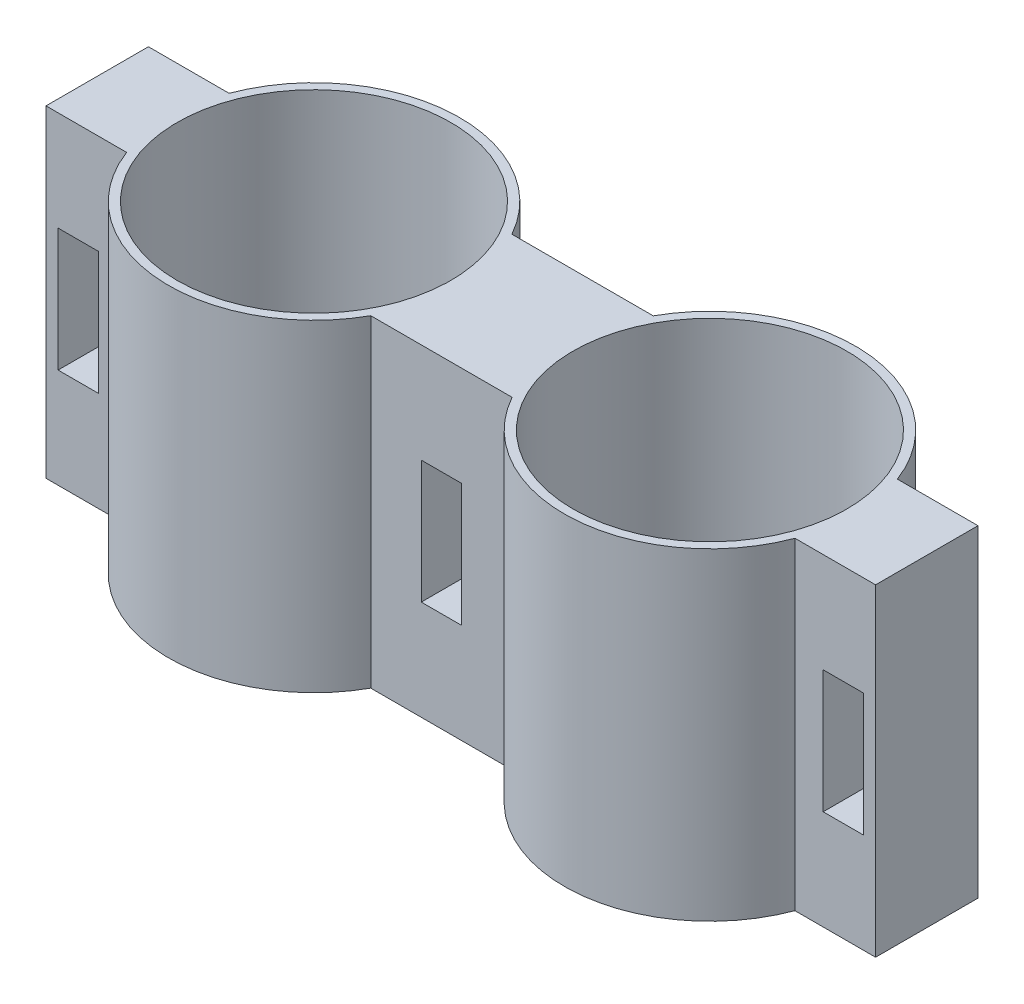
SolidWorks part; units mm, degrees
ref_plane "Front Plane" through (0, 0, 0) normal (0, 0, 1) x (1, 0, 0)
ref_plane "Top Plane" through (0, 0, 0) normal (0, 1, 0) x (1, 0, 0)
ref_plane "Right Plane" through (0, 0, 0) normal (1, 0, 0) x (0, 0, -1)
sketch "Sketch1" plane through (0, 0, 0) normal (0, 1, 0) x (1, 0, 0)
  line L0 (-49.0921, 0) -> (49.0921, 0) construction
  line L1 (-20, 17.5) -> (-20, -17.5) construction
  line L2 (-17.5289, -17.5) -> (17.5289, -17.5) construction
  line L3 (20, -17.5) -> (20, 17.5) construction
  line L4 (17.5289, 17.5) -> (-17.5289, 17.5) construction
  line L5 (-17.5289, 17.5) -> (17.5289, 17.5)
  line L6 (-17.5289, -17.5) -> (17.5289, -17.5)
  line L7 (-17.5289, 17.5) -> (17.5289, -17.5) construction
  line L8 (0, 17.5) -> (0, -17.5) construction
  line L9 (-82.8738, -12.7) -> (-82.8738, 12.7) construction
  line L10 (-82.8738, -12.7) -> (-102.8738, -12.7)
  line L11 (-82.8738, -12.7) -> (-82.8738, 12.7)
  line L12 (-82.8738, 12.7) -> (-102.8738, 12.7)
  line L13 (-102.8738, -12.7) -> (-102.8738, 12.7)
  line L14 (82.8738, -12.7) -> (82.8738, 12.7)
  line L15 (82.8738, -12.7) -> (102.8738, -12.7)
  line L16 (82.8738, 12.7) -> (102.8738, 12.7)
  line L17 (102.8738, -12.7) -> (102.8738, 12.7)
  arc A0 (-17.5289, 17.5) -> (-17.5289, -17.5) centre (-49.0921, 0) ccw
  arc A1 (-20, 17.5) -> (-20, -17.5) centre (-49.0921, 0) ccw
  arc A2 (20, -17.5) -> (20, 17.5) centre (49.0921, 0) ccw
  arc A3 (17.5289, -17.5) -> (17.5289, 17.5) centre (49.0921, 0) ccw
  point P21 (0, -17.5)
  dimension "D3" = 67.9
  dimension "D4" = 2.14
  dimension "D5" = 67.9
  dimension "D6" = 2.14
  dimension "D1" = 40
  dimension "D2" = 35
  dimension "D7" = 98.1843
  dimension "D8" = 35
  dimension "D9" = 35.0578
  dimension "D10" = 25.4
  dimension "D11" = 20
  dimension "D12" = 35
extrude "Boss-Extrude1" add sketch "Sketch1" along normal blind 80 contours A0 L6 A3 L5 | L11 L10 L13 L12 | L14 L16 L17 L15
sketch "Sketch2" plane through (0, 80, 0) normal (0, 1, 0) x (1, 0, 0)
  line L0 (-49.1082, 0) -> (49.0921, 0) construction
  circle A0 centre (-49.1082, 0) radius 33.95
  circle A1 centre (49.0921, 0) radius 33.95
  dimension "D1" = 67.9
  dimension "D2" = 98.2003
extrude "Cut-Extrude1" cut sketch "Sketch2" against normal blind 80
sketch "Sketch3" plane through (0, 0, 12.7) normal (0, 0, 1) x (1, 0, 0)
  line L0 (-94.8738, 80) -> (-94.8738, 0) construction
  line L2 (-5, 24.75) -> (5, 24.75)
  line L3 (0, 80) -> (0, 0) construction
  line L4 (-17.5289, 80) -> (17.5289, 80) construction
  line L5 (-5, 24.75) -> (-5, 55.25)
  line L6 (-82.8738, 80) -> (-102.8738, 80) construction
  line L7 (-82.8738, 0) -> (-102.8738, 0) construction
  line L8 (-102.8738, 80) -> (-102.8738, 0) construction
  line L9 (94.8738, 80) -> (94.8738, 0) construction
  line L10 (-99.8738, 24.75) -> (-89.8738, 24.75)
  line L11 (-99.8738, 24.75) -> (-99.8738, 55.25)
  line L12 (-99.8738, 55.25) -> (-89.8738, 55.25)
  line L13 (-89.8738, 24.75) -> (-89.8738, 55.25)
  line L14 (-99.8738, 24.75) -> (-89.8738, 55.25) construction
  line L15 (-99.8738, 55.25) -> (-89.8738, 24.75) construction
  line L16 (99.8738, 24.75) -> (89.8738, 55.25) construction
  line L17 (99.8738, 55.25) -> (89.8738, 24.75) construction
  line L18 (99.8738, 24.75) -> (89.8738, 24.75)
  line L19 (99.8738, 24.75) -> (99.8738, 55.25)
  line L20 (89.8738, 24.75) -> (89.8738, 55.25)
  line L21 (99.8738, 55.25) -> (89.8738, 55.25)
  line L22 (-5, 55.25) -> (5, 55.25)
  line L23 (5, 24.75) -> (5, 55.25)
  line L24 (-5, 24.75) -> (5, 55.25) construction
  line L25 (-5, 55.25) -> (5, 24.75) construction
  point P13 (-94.8738, 40)
  point P24 (0, 40)
  point P29 (0, 0)
  dimension "D1" = 8
  dimension "D2" = 30.5
  dimension "D3" = 10
  dimension "D4" = 10
  dimension "D5" = 30.5
extrude "Cut-Extrude3" cut sketch "Sketch3" against normal through all both and the other way through all
